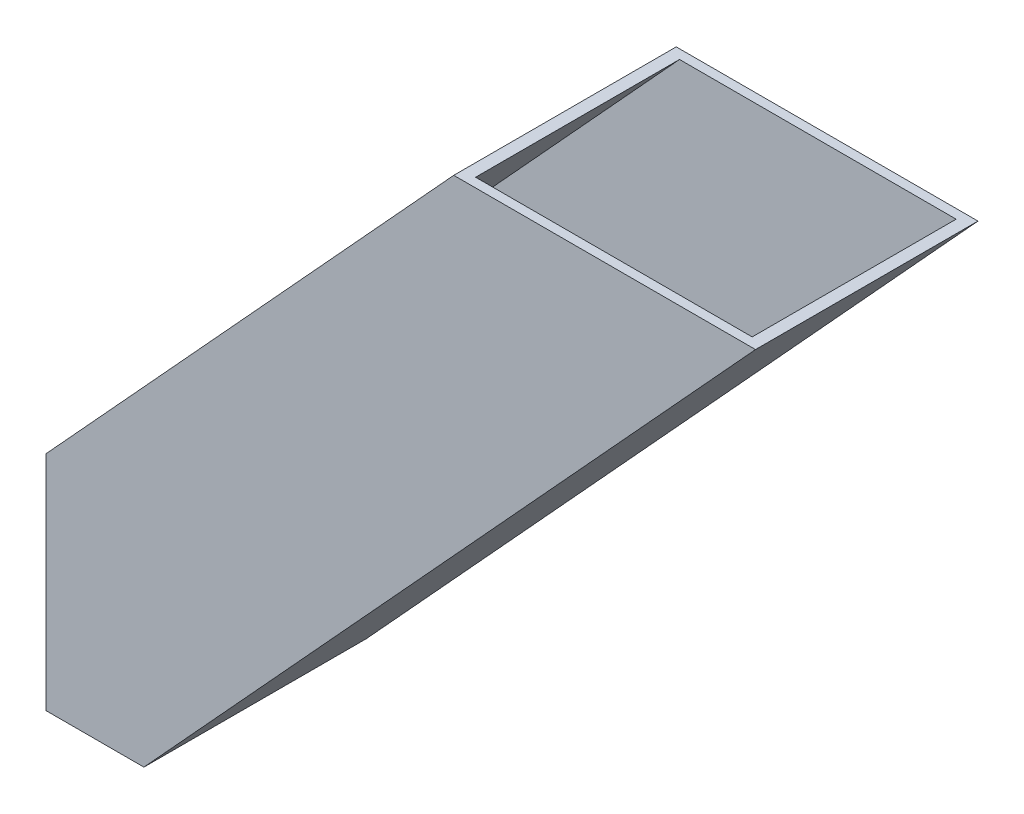
SolidWorks part; units mm, degrees
ref_plane "Front Plane" through (0, 0, 0) normal (0, 0, 1) x (1, 0, 0)
ref_plane "Top Plane" through (0, 0, 0) normal (0, 1, 0) x (1, 0, 0)
ref_plane "Right Plane" through (0, 0, 0) normal (1, 0, 0) x (0, 0, -1)
sketch "Sketch2" plane through (0, 0, 0) normal (0, 0, 1) x (1, 0, 0)
  line L0 (-149.5904, -106.8557) -> (93.4096, 158.3353)
  line L1 (93.4096, 158.3353) -> (149.5904, 106.8557)
  line L2 (149.5904, 106.8557) -> (-93.4096, -158.3353)
  line L3 (-93.4096, -158.3353) -> (-149.5904, -106.8557)
  line L4 (-93.4096, -158.3353) -> (-93.4096, -45.5443)
  line L5 (149.5904, 106.8557) -> (46.2377, 106.8557)
  line L6 (-28.0904, 25.7398) -> (28.0904, -25.7398) construction
  point P2 (0, 0)
  dimension "D1" = 76.2
  dimension "D2" = 152.4
  dimension "D3" = 243
extrude "Boss-Extrude1" add sketch "Sketch2" along normal mid plane 76.2 contours L0 L6 L2 L5 | L6 L0 L4 L2
shell "Shell1" thickness 3.175
sketch "Sketch3" plane through (0, 0, 38.1) normal (0, 0, 1) x (1, 0, 0)
  line L0 (-93.4096, -121.7443) -> (-59.8805, -121.7443)
  line L1 (-93.4096, -158.3353) -> (-93.4096, -45.5443) construction
  line L2 (149.5904, 106.8557) -> (-93.4096, -158.3353) construction
  line L3 (-93.4096, -158.3353) -> (-93.4096, -45.5443)
  line L4 (149.5904, 106.8557) -> (-93.4096, -158.3353)
  line L5 (-93.4096, -45.5443) -> (46.2377, 106.8557) construction
  line L6 (-93.4096, -45.5443) -> (46.2377, 106.8557)
  line L7 (149.5904, 106.8557) -> (46.2377, 106.8557) construction
  line L8 (149.5904, 106.8557) -> (46.2377, 106.8557)
  line L9 (-93.4096, -121.7443) -> (-93.4096, -158.3353)
  line L10 (-59.8805, -121.7443) -> (-93.4096, -121.7443)
  line M3 (-93.4096, -45.5443) -> (-93.4096, -158.3353)
  line M4 (-93.4096, -158.3353) -> (149.5904, 106.8557)
  dimension "D1" = 76.2
extrude "Cut-Extrude6" cut sketch "Sketch3" against normal blind 76.2 contours L0 M3 M4
